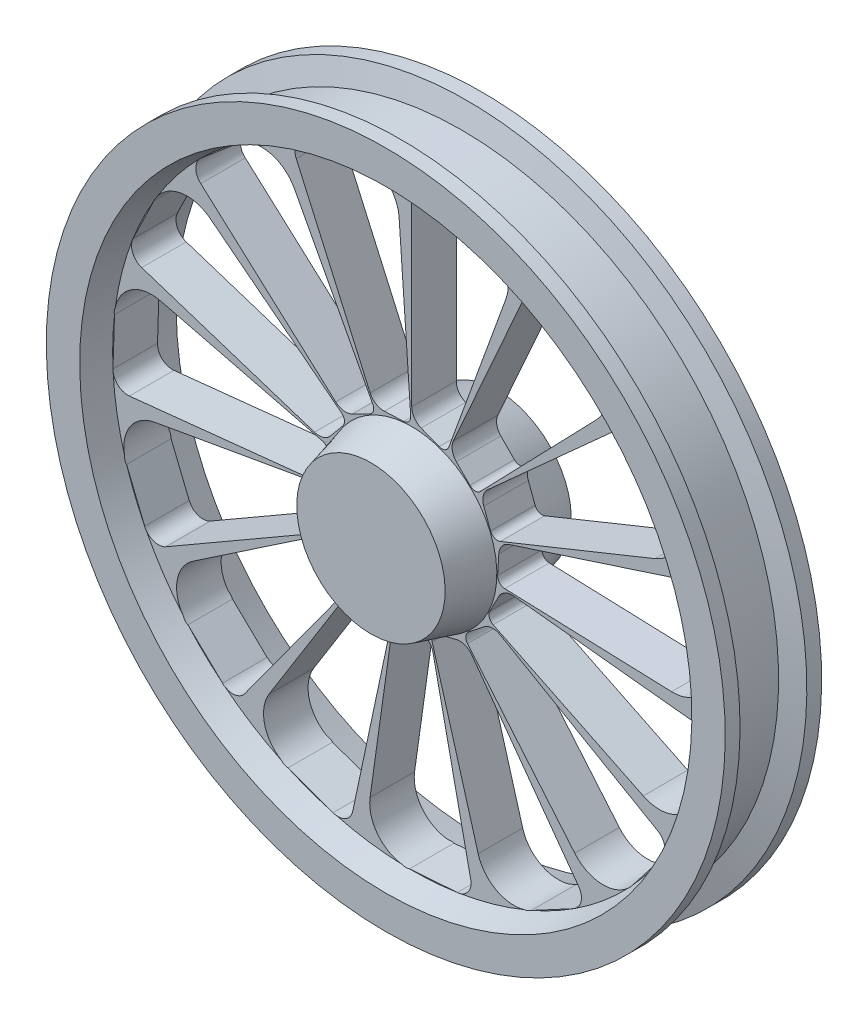
SolidWorks part; units mm, degrees
material "1060 Alloy"
ref_plane "Front Plane" through (0, 0, 0) normal (0, 0, 1) x (1, 0, 0)
ref_plane "Top Plane" through (0, 0, 0) normal (0, 1, 0) x (1, 0, 0)
ref_plane "Right Plane" through (0, 0, 0) normal (1, 0, 0) x (0, 0, -1)
sketch "Sketch1" plane through (0, 0, 0) normal (1, 0, 0) x (0, 0, -1)
  line L0 (-313.7514, 0) -> (373.7677, 0) construction
  line L1 (-70.595, 0) -> (-70.595, 100)
  line L2 (-70.595, 100) -> (-15.595, 114.7372)
  line L3 (-15.595, 114.7372) -> (-15.595, 403.1218)
  line L4 (-15.595, 403.1218) -> (-50.595, 412.5)
  line L5 (-50.595, 412.5) -> (-50.595, 457.5)
  line L6 (-50.595, 457.5) -> (-30.595, 457.5)
  line L7 (-30.595, 457.5) -> (-22.5565, 427.5)
  line L17 (-22.5565, 427.5) -> (51.3665, 427.5)
  line L18 (14.405, 427.5) -> (14.405, 0) construction
  line L19 (14.405, 0) -> (-70.595, 0) construction
  line L20 (-70.595, 0) -> (14.405, 0)
  line L21 (59.405, 457.5) -> (51.3665, 427.5)
  line L22 (79.405, 457.5) -> (59.405, 457.5)
  line L23 (79.405, 412.5) -> (79.405, 457.5)
  line L24 (44.405, 403.1218) -> (79.405, 412.5)
  line L25 (44.405, 114.7372) -> (44.405, 403.1218)
  line L26 (99.405, 100) -> (44.405, 114.7372)
  line L27 (99.405, 0) -> (99.405, 100)
  line L28 (14.405, 0) -> (99.405, 0)
  dimension "D1" = 65
  dimension "D2" = 30
  dimension "D3" = 100
  dimension "D4" = 45
  dimension "D5" = 30
  dimension "D6" = 20
  dimension "D7" = 85
  dimension "D8" = 15
  dimension "D9" = 15
  dimension "D10" = 457.5
  dimension "D11" = 14.405
revolve "Revolve1" add sketch "Sketch1" angle 360 about L20
sketch "Sketch2" plane through (0, 0, 0) normal (0, 0, 1) x (1, 0, 0)
  line L0 (0, 623.3879) -> (0, -729.0545) construction
  line L1 (-508.8294, 0) -> (523.4024, 0) construction
  line L2 (0, 382.6672) -> (0, 137.8357)
  line L3 (22.7249, 402.4807) -> (86.7695, 393.6727)
  line L4 (126.9418, 327.038) -> (49.9825, 115.5941)
  line L5 (12.6935, 119.2181) -> (36.9323, 109.7055)
  line L6 (184.4639, 358.4414) -> (239.389, 324.3456)
  line L7 (248.9854, 247.1322) -> (92.6777, 85.2707)
  line L8 (60.0864, 103.7483) -> (78.3606, 85.1992)
  line L9 (155.6448, 349.5839) -> (56.0628, 125.9192)
  line L10 (314.3074, 252.4243) -> (350.616, 198.9362)
  line L11 (327.9772, 124.495) -> (119.348, 40.2033)
  line L12 (97.0899, 70.3394) -> (106.2396, 45.9612)
  line L13 (284.3772, 256.0544) -> (102.4319, 92.2301)
  line L14 (389.8043, 102.7607) -> (401.2183, 39.1288)
  line L15 (350.2588, -19.6685) -> (125.382, -11.8157)
  line L16 (117.3057, 24.7682) -> (115.7488, -1.2239)
  line L17 (363.9382, 118.2507) -> (131.0895, 42.5936)
  line L18 (397.9005, -64.6711) -> (382.4463, -127.4442)
  line L19 (311.9774, -160.4312) -> (109.7362, -61.7916)
  line L20 (117.2382, -25.0856) -> (105.244, -48.1974)
  line L21 (380.5709, -39.9996) -> (137.0806, -14.4078)
  line L22 (337.1961, -220.9207) -> (297.5458, -271.981)
  line L23 (219.7523, -273.4538) -> (75.1162, -101.0832)
  line L24 (96.8992, -70.6019) -> (76.5416, -86.8371)
  line L25 (331.3996, -191.3336) -> (119.3692, -68.9178)
  line L26 (218.1874, -338.9711) -> (161.197, -369.4898)
  line L27 (89.53, -339.1938) -> (27.5078, -122.8966)
  line L28 (59.8054, -103.9105) -> (34.6044, -110.4619)
  line L29 (224.9262, -309.5843) -> (81.0178, -111.5114)
  line L30 (61.4521, -398.4103) -> (-3.0242, -403.1104)
  line L31 (-56.1728, -346.2841) -> (-24.8569, -123.46)
  line L32 (12.3707, -119.252) -> (-13.3162, -114.9868)
  line L33 (79.561, -374.305) -> (28.6577, -134.8237)
  line L34 (-105.9088, -388.9608) -> (-166.7226, -367.0296)
  line L35 (-192.1628, -293.4987) -> (-72.9236, -102.6761)
  line L36 (-37.2029, -113.9738) -> (-58.9343, -99.6295)
  line L37 (-79.561, -374.305) -> (-28.6577, -134.8237)
  line L38 (-254.9571, -312.2564) -> (-301.593, -267.4861)
  line L39 (-294.9262, -189.9648) -> (-108.3812, -64.1386)
  line L40 (-80.3439, -88.9884) -> (-94.3622, -67.0453)
  line L41 (-224.9262, -309.5843) -> (-81.0178, -111.5114)
  line L42 (-359.921, -181.56) -> (-384.3153, -121.6918)
  line L43 (-346.6941, -53.5842) -> (-125.0987, -14.5109)
  line L44 (-109.5926, -48.6162) -> (-113.4739, -22.8684)
  line L45 (-331.3996, -191.3336) -> (-119.3692, -68.9178)
  line L46 (-402.6513, -19.4702) -> (-400.586, 45.1442)
  line L47 (-338.5155, 92.0616) -> (-120.1854, 37.6258)
  line L48 (-119.8918, 0.1622) -> (-112.965, 25.2627)
  line L49 (-380.5709, -39.9996) -> (-137.0806, -14.4078)
  line L50 (-375.7595, 145.9861) -> (-347.5918, 204.1743)
  line L51 (-271.8044, 221.7891) -> (-94.4911, 83.2567)
  line L52 (-109.4607, 48.9126) -> (-92.9234, 69.0256)
  line L53 (-363.9382, 118.2507) -> (-131.0895, 42.5936)
  line L54 (-283.8955, 286.2001) -> (-234.4957, 327.9008)
  line L55 (-158.0959, 313.1673) -> (-52.4583, 114.4918)
  line L56 (-80.1027, 89.2056) -> (-56.8145, 100.8534)
  line L57 (-284.3772, 256.0544) -> (-102.4319, 92.2301)
  line L58 (-142.9434, 376.9275) -> (-80.8532, 394.9303)
  line L59 (-17.0512, 350.3959) -> (-1.355, 125.9302)
  line L60 (-36.8943, 114.0741) -> (-10.8819, 115.2427)
  line L61 (-155.6448, 349.5839) -> (-56.0628, 125.9192)
  circle A0 centre (0, 0) radius 403.1218 construction
  arc A1 (0, 382.6672) -> (22.7249, 402.4807) centre (20, 382.6672) cw
  arc A2 (86.7695, 393.6727) -> (126.9418, 327.038) centre (79.9572, 344.139) cw
  arc A3 (49.9825, 115.5941) -> (36.9323, 109.7055) centre (40.5856, 119.0143) cw
  arc A4 (0, 137.8357) -> (12.6935, 119.2181) centre (20, 137.8357) ccw
  arc A5 (155.6448, 349.5839) -> (184.4639, 358.4414) centre (173.9157, 341.4492) cw
  arc A6 (239.389, 324.3456) -> (248.9854, 247.1322) centre (213.0184, 281.8651) cw
  arc A7 (56.0628, 125.9192) -> (60.0864, 103.7483) centre (74.3337, 117.7844) ccw
  arc A8 (92.6777, 85.2707) -> (78.3606, 85.1992) centre (85.4843, 92.2173) cw
  arc A9 (284.3772, 256.0544) -> (314.3074, 252.4243) centre (297.7598, 241.1915) cw
  arc A10 (350.616, 198.9362) -> (327.9772, 124.495) centre (309.2469, 170.8542) cw
  arc A11 (102.4319, 92.2301) -> (97.0899, 70.3394) centre (115.8145, 77.3672) ccw
  arc A12 (119.348, 40.2033) -> (106.2396, 45.9612) centre (115.6019, 49.4751) cw
  arc A13 (363.9382, 118.2507) -> (389.8043, 102.7607) centre (370.1185, 99.2296) cw
  arc A14 (401.2183, 39.1288) -> (350.2588, -19.6685) centre (352.0037, 30.301) cw
  arc A15 (131.0895, 42.5936) -> (117.3057, 24.7682) centre (137.2699, 23.5724) ccw
  arc A16 (125.382, -11.8157) -> (115.7488, -1.2239) centre (125.7309, -1.8218) cw
  arc A17 (380.5709, -39.9996) -> (397.9005, -64.6711) centre (378.4804, -59.8901) cw
  arc A18 (382.4463, -127.4442) -> (311.9774, -160.4312) centre (333.896, -115.4915) cw
  arc A19 (137.0806, -14.4078) -> (117.2382, -25.0856) centre (134.99, -34.2982) ccw
  arc A20 (109.7362, -61.7916) -> (105.244, -48.1974) centre (114.12, -52.8036) cw
  arc A21 (331.3996, -191.3336) -> (337.1961, -220.9207) centre (321.3996, -208.6541) cw
  arc A22 (297.5458, -271.981) -> (219.7523, -273.4538) centre (258.0545, -241.3144) cw
  arc A23 (119.3692, -68.9178) -> (96.8992, -70.6019) centre (109.3692, -86.2384) ccw
  arc A24 (75.1162, -101.0832) -> (76.5416, -86.8371) centre (82.7766, -94.6553) cw
  arc A25 (224.9262, -309.5843) -> (218.1874, -338.9711) centre (208.7458, -321.34) cw
  arc A26 (161.197, -369.4898) -> (89.53, -339.1938) centre (137.5931, -325.4119) cw
  arc A27 (81.0178, -111.5114) -> (59.8054, -103.9105) centre (64.8374, -123.2671) ccw
  arc A28 (27.5078, -122.8966) -> (34.6044, -110.4619) centre (37.1204, -120.1402) cw
  arc A29 (79.561, -374.305) -> (61.4521, -398.4103) centre (59.998, -378.4633) cw
  arc A30 (-3.0242, -403.1104) -> (-56.1728, -346.2841) centre (-6.6594, -353.2428) cw
  arc A31 (28.6577, -134.8237) -> (12.3707, -119.252) centre (9.0947, -138.9819) ccw
  arc A32 (-24.8569, -123.46) -> (-13.3162, -114.9868) centre (-14.9542, -124.8518) cw
  arc A33 (-79.561, -374.305) -> (-105.9088, -388.9608) centre (-99.1239, -370.1468) cw
  arc A34 (-166.7226, -367.0296) -> (-192.1628, -293.4987) centre (-149.7604, -319.9947) cw
  arc A35 (-28.6577, -134.8237) -> (-37.2029, -113.9738) centre (-48.2206, -130.6654) ccw
  arc A36 (-72.9236, -102.6761) -> (-58.9343, -99.6295) centre (-64.4432, -107.9753) cw
  arc A37 (-224.9262, -309.5843) -> (-254.9571, -312.2564) centre (-241.1065, -297.8286) cw
  arc A38 (-301.593, -267.4861) -> (-294.9262, -189.9648) centre (-266.9665, -231.4166) cw
  arc A39 (-81.0178, -111.5114) -> (-80.3439, -88.9884) centre (-97.1981, -99.7557) ccw
  arc A40 (-108.3812, -64.1386) -> (-94.3622, -67.0453) centre (-102.7893, -72.429) cw
  arc A41 (-331.3996, -191.3336) -> (-359.921, -181.56) centre (-341.3996, -174.0131) cw
  arc A42 (-384.3153, -121.6918) -> (-346.6941, -53.5842) centre (-338.0117, -102.8245) cw
  arc A43 (-119.3692, -68.9178) -> (-109.5926, -48.6162) centre (-129.3692, -51.5973) ccw
  arc A44 (-125.0987, -14.5109) -> (-113.4739, -22.8684) centre (-123.3622, -24.359) cw
  arc A45 (-380.5709, -39.9996) -> (-402.6513, -19.4702) centre (-382.6615, -20.1092) cw
  arc A46 (-400.586, 45.1442) -> (-338.5155, 92.0616) centre (-350.6116, 43.5468) cw
  arc A47 (-137.0806, -14.4078) -> (-119.8918, 0.1622) centre (-139.1712, 5.4827) ccw
  arc A48 (-120.1854, 37.6258) -> (-112.965, 25.2627) centre (-122.6047, 27.9229) cw
  arc A49 (-363.9382, 118.2507) -> (-375.7595, 145.9861) centre (-357.7578, 137.2718) cw
  arc A50 (-347.5918, 204.1743) -> (-271.8044, 221.7891) centre (-302.5875, 182.3886) cw
  arc A51 (-131.0895, 42.5936) -> (-109.4607, 48.9126) centre (-124.9092, 61.6147) ccw
  arc A52 (-94.4911, 83.2567) -> (-92.9234, 69.0256) centre (-100.6477, 75.3766) cw
  arc A53 (-284.3772, 256.0544) -> (-283.8955, 286.2001) centre (-270.9946, 270.9173) cw
  arc A54 (-234.4957, 327.9008) -> (-158.0959, 313.1673) centre (-202.2433, 289.6937) cw
  arc A55 (-102.4319, 92.2301) -> (-80.1027, 89.2056) centre (-89.0493, 107.093) ccw
  arc A56 (-52.4583, 114.4918) -> (-56.8145, 100.8534) centre (-61.2878, 109.7971) cw
  arc A57 (-155.6448, 349.5839) -> (-142.9434, 376.9275) centre (-137.3739, 357.7187) cw
  arc A58 (-80.8532, 394.9303) -> (-17.0512, 350.3959) centre (-66.9294, 346.9081) cw
  arc A59 (-56.0628, 125.9192) -> (-36.8943, 114.0741) centre (-37.7919, 134.0539) ccw
  arc A60 (-1.355, 125.9302) -> (-10.8819, 115.2427) centre (-11.3307, 125.2326) cw
  point P16 (379.7344, -97.4558)
  point P25 (0, 124.1997)
  point P190 (0, 0)
  dimension "D1" = 20
  dimension "D3" = 10
  dimension "D4" = 20
  dimension "D2" = 50
  dimension "D5" = 20
  dimension "D6" = 15
  dimension "D7" = 9.0947
  dimension "D8" = 12.3707
  dimension "D9" = 22.7249
extrude "Cut-Extrude1" cut sketch "Sketch2" against normal mid plane 260 contours A52 L51 A50 L50 A49 L53 A51 L52 | A56 L55 A54 L54 A53 L57 A55 L56 | A60 L59 A58 L58 A57 L61 A59 L60 | L2 A4 L5 A3 L4 A2 L3 A1 | A8 L7 A6 L6 A5 L9 A7 L8 | A12 L11 A10 L10 A9 L13 A11 L12 | A16 L15 A14 L14 A13 L17 A15 L16 | A20 L19 A18 L18 A17 L21 A19 L20 | A24 L23 A22 L22 A21 L25 A23 L24 | A28 L27 A26 L26 A25 L29 A27 L28 | A32 L31 A30 L30 A29 L33 A31 L32 | A36 L35 A34 L34 A33 L37 A35 L36 | A40 L39 A38 L38 A37 L41 A39 L40 | A44 L43 A42 L42 A41 L45 A43 L44 | A48 L47 A46 L46 A45 L49 A47 L48
equation "\"A\"= 130.0"
equation "\"B\"= 915.0"
